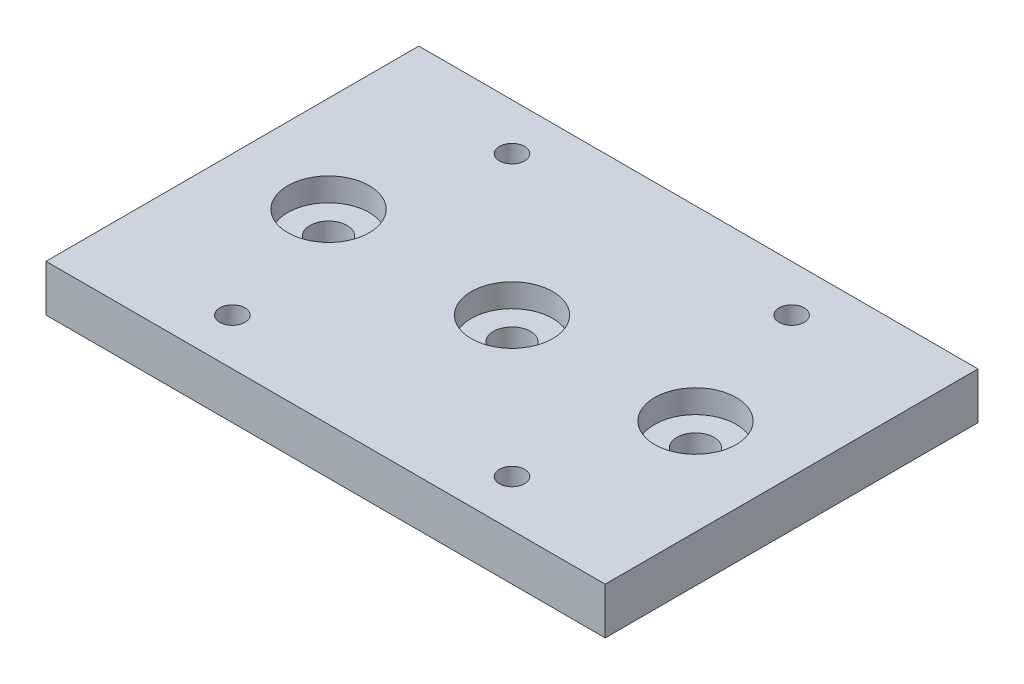
SolidWorks part; units mm, degrees
ref_plane "Front Plane" through (0, 0, 0) normal (0, 0, 1) x (1, 0, 0)
ref_plane "Top Plane" through (0, 0, 0) normal (0, 1, 0) x (1, 0, 0)
ref_plane "Right Plane" through (0, 0, 0) normal (1, 0, 0) x (0, 0, -1)
sketch "Sketch1" plane through (0, 0, 0) normal (0, 1, 0) x (1, 0, 0)
  line L1 (-76.2, -50.8) -> (76.2, -50.8)
  line L2 (-76.2, -50.8) -> (-76.2, 50.8)
  line L3 (-76.2, 50.8) -> (76.2, 50.8)
  line L4 (76.2, -50.8) -> (76.2, 50.8)
  line L5 (-76.2, -50.8) -> (76.2, 50.8) construction
  line L6 (-76.2, 50.8) -> (76.2, -50.8) construction
  point P0 (0, 0)
  dimension "D1" = 152.4
  dimension "D2" = 101.6
extrude "Boss-Extrude1" add sketch "Sketch1" along normal blind 12.7
hole_wizard "CBORE for 3/8 Hex Head Bolt1" positions "Sketch2" profile "Sketch3" counterbore size "3/8" standard "ANSI Inch" end condition through all
sketch "Sketch2" plane through (0, 12.7, 0) normal (0, 1, 0) x (1, 0, 0)
  line L1 (-76.2, 0) -> (76.2, 0) construction
  line L2 (-76.2, 50.8) -> (-76.2, -50.8) construction
  line L3 (76.2, -50.8) -> (76.2, 50.8) construction
  point P0 (-50, 0)
  point P2 (50, 0)
  point P4 (0, 0)
  point P16 (0, 0)
  point P17 (0, 0)
  point P18 (91.4301, 20.2452)
  point P19 (0, 0)
  point P20 (33.4373, 0)
  dimension "D1" = 50
  dimension "D2" = 50
sketch "Sketch3" plane through (-50, 12.7, 0) normal (1, 0, 0) x (0, 0, 1)
  line L0 (0, 0) -> (0, 12.7)
  line L1 (0, 12.7) -> (5.0419, 12.7)
  line L3 (5.0419, 12.7) -> (5.0419, 6.35)
  line L4 (5.0419, 6.35) -> (11.1125, 6.35)
  line L5 (11.1125, 6.35) -> (11.1125, 0)
  line L7 (11.1125, 0) -> (0, 0)
  line L11 (0, -6.35) -> (0, 107.95) construction
  dimension "Thru Hole Dia." = 10.0838
  dimension "Thru Hole Depth" = 12.7
  dimension "C'Bore Dia." = 22.225
  dimension "C'Bore Depth" = 6.35
hole_wizard "1/4 (0.25) Diameter Hole2" positions "Sketch4" profile "Sketch5" hole size "1/4" standard "ANSI Inch" end condition through all
sketch "Sketch4" plane through (0, 0, 0) normal (0, 1, 0) x (1, 0, 0)
  point P6 (-38.1, 38.1)
  point P33 (38.1, 38.1)
  point P34 (38.1, -38.1)
  point P35 (-38.1, -38.1)
  dimension "D1" = 38.1
  dimension "D2" = 38.1
  dimension "D3" = 2
  dimension "D4" = 2
sketch "Sketch5" plane through (-38.1, 0, -38.1) normal (1, 0, 0) x (0, 0, -1)
  line L0 (0, 0) -> (0, 12.7)
  line L1 (0, 12.7) -> (3.429, 12.7)
  line L2 (3.429, 12.7) -> (3.429, 0)
  line L5 (3.429, 0) -> (0, 0)
  line L11 (0, -6.35) -> (0, 107.95) construction
  dimension "Thru Hole Dia." = 6.858
  dimension "Thru Hole Depth" = 12.7
sketch "Sketch6" plane through (0, 0, 0) normal (0, -1, 0) x (1, 0, 0)
  line L1 (38.17, -31.7579) -> (32.6426, -34.8683)
  line L2 (32.6426, -34.8683) -> (32.5726, -41.2104)
  line L3 (32.5726, -41.2104) -> (38.03, -44.4421)
  line L4 (38.03, -44.4421) -> (43.5574, -41.3317)
  line L5 (43.5574, -41.3317) -> (43.6274, -34.9896)
  line L6 (43.6274, -34.9896) -> (38.17, -31.7579)
  line L7 (-38.2035, -31.7584) -> (-43.6438, -35.0188)
  line L8 (-43.6438, -35.0188) -> (-43.5403, -41.3605)
  line L9 (-43.5403, -41.3605) -> (-37.9965, -44.4416)
  line L10 (-37.9965, -44.4416) -> (-32.5562, -41.1812)
  line L11 (-32.5562, -41.1812) -> (-32.6597, -34.8395)
  line L12 (-32.6597, -34.8395) -> (-38.2035, -31.7584)
  line L13 (-38.2145, 44.4414) -> (-43.6491, 41.1715)
  line L14 (-43.6491, 41.1715) -> (-43.5346, 34.8301)
  line L15 (-43.5346, 34.8301) -> (-37.9855, 31.7586)
  line L16 (-37.9855, 31.7586) -> (-32.5509, 35.0285)
  line L17 (-32.5509, 35.0285) -> (-32.6654, 41.3699)
  line L18 (-32.6654, 41.3699) -> (-38.2145, 44.4414)
  line L19 (38.0535, 44.4423) -> (32.5841, 41.2309)
  line L20 (32.5841, 41.2309) -> (32.6306, 34.8886)
  line L21 (32.6306, 34.8886) -> (38.1465, 31.7577)
  line L22 (38.1465, 31.7577) -> (43.6159, 34.9691)
  line L23 (43.6159, 34.9691) -> (43.5694, 41.3114)
  line L24 (43.5694, 41.3114) -> (38.0535, 44.4423)
  circle A0 centre (38.1, -38.1) radius 5.4927 construction
  circle A1 centre (-38.1, -38.1) radius 5.4927 construction
  circle A2 centre (-38.1, 38.1) radius 5.4928 construction
  circle A3 centre (38.1, 38.1) radius 5.4928 construction
  point P28 (40.8987, -33.3737)
  dimension "D1" = 10.9855
extrude "Cut-Extrude1" cut sketch "Sketch6" against normal blind 6.35
